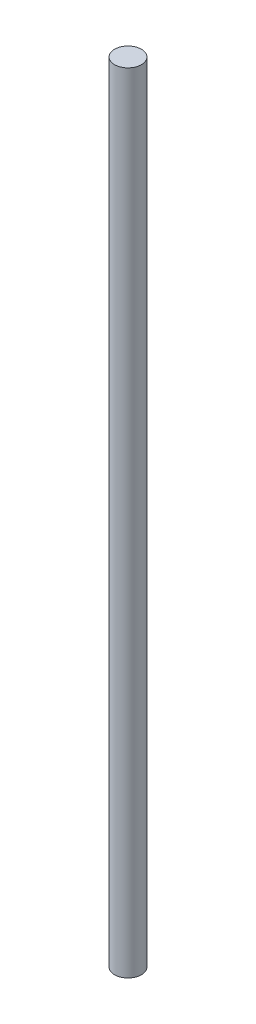
SolidWorks part; units mm, degrees
ref_plane "前视基准面" through (0, 0, 0) normal (0, 0, 1) x (1, 0, 0)
ref_plane "上视基准面" through (0, 0, 0) normal (0, 1, 0) x (1, 0, 0)
ref_plane "右视基准面" through (0, 0, 0) normal (1, 0, 0) x (0, 0, -1)
sketch "草图1" plane through (0, 0, 0) normal (0, 1, 0) x (1, 0, 0)
  circle A0 centre (0, 0) radius 8.5
  dimension "D1" = 17
extrude "凸台-拉伸1" add sketch "草图1" along normal blind 500
